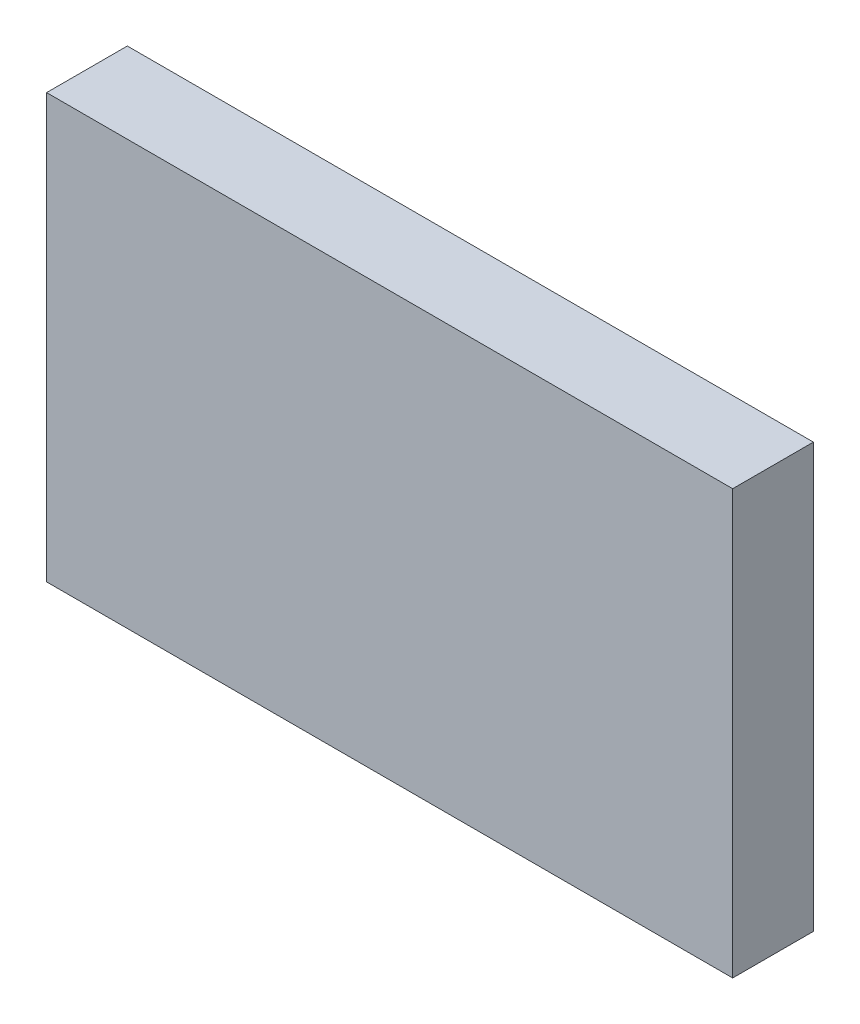
SolidWorks part; units mm, degrees
material "Custom Plastic"
ref_plane "Front Plane" through (0, 0, 0) normal (0, 0, 1) x (1, 0, 0)
ref_plane "Top Plane" through (0, 0, 0) normal (0, 1, 0) x (1, 0, 0)
ref_plane "Right Plane" through (0, 0, 0) normal (1, 0, 0) x (0, 0, -1)
sketch "Sketch1" plane through (0, 0, 0) normal (0, 0, 1) x (1, 0, 0)
  line L1 (-85, -52.5) -> (85, -52.5)
  line L2 (-85, -52.5) -> (-85, 52.5)
  line L3 (-85, 52.5) -> (85, 52.5)
  line L4 (85, -52.5) -> (85, 52.5)
  line L5 (-85, -52.5) -> (85, 52.5) construction
  line L6 (-85, 52.5) -> (85, -52.5) construction
  point P0 (0, 0)
extrude "Boss-Extrude1" add sketch "Sketch1" along normal blind 20
